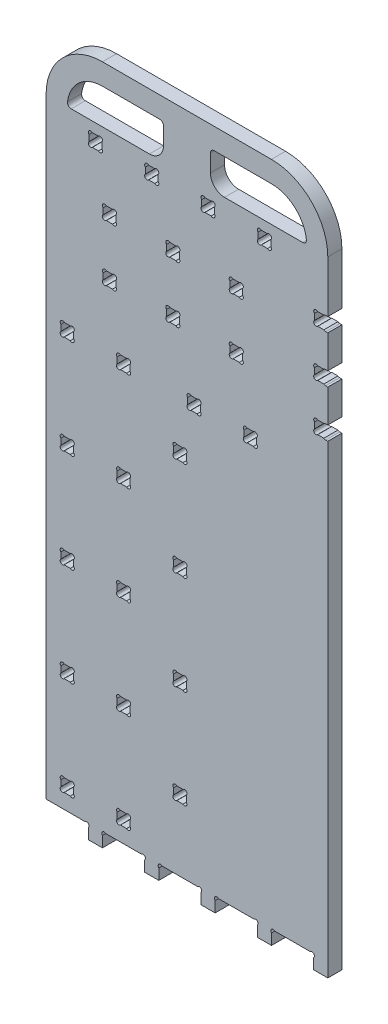
SolidWorks part; units mm, degrees
ref_plane "Front Plane" through (0, 0, 0) normal (0, 0, 1) x (1, 0, 0)
ref_plane "Top Plane" through (0, 0, 0) normal (0, 1, 0) x (1, 0, 0)
ref_plane "Right Plane" through (0, 0, 0) normal (1, 0, 0) x (0, 0, -1)
sketch "Sketch1" plane through (0, 0, 0) normal (0, 0, 1) x (1, 0, 0)
  line L0 (76.2, 869.95) -> (304.8, 869.95)
  line L1 (381, 793.75) -> (381, 723.9)
  line L11 (381, -50.8) -> (361.95, -50.8)
  line L12 (361.95, -50.8) -> (361.95, -36.2401)
  line L13 (309.2901, -31.75) -> (357.4599, -31.75)
  line L14 (304.8, -50.8) -> (304.8, -36.2401)
  line L15 (285.75, -50.8) -> (285.75, -36.2401)
  line L16 (233.0901, -31.75) -> (281.2599, -31.75)
  line L17 (228.6, -50.8) -> (228.6, -36.2401)
  line L18 (209.55, -50.8) -> (209.55, -36.2401)
  line L19 (156.8901, -31.75) -> (205.0599, -31.75)
  line L20 (152.4, -50.8) -> (152.4, -36.2401)
  line L21 (133.35, -50.8) -> (133.35, -36.2401)
  line L22 (80.6901, -31.75) -> (128.8599, -31.75)
  line L23 (76.2, -50.8) -> (76.2, -36.2401)
  line L24 (57.15, -50.8) -> (57.15, -36.2401)
  line L25 (381, -50.8) -> (381, 577.85)
  line L26 (52.6599, -31.75) -> (0, -31.75)
  line L27 (381, 704.85) -> (381, 660.4)
  line L28 (0, -31.75) -> (0, 793.75)
  line L29 (158.75, 812.8) -> (158.75, 836.295)
  line L30 (153.67, 841.375) -> (76.2, 841.375)
  line L31 (33.9594, 793.75) -> (139.7, 793.75)
  line L32 (227.33, 841.375) -> (304.8, 841.375)
  line L33 (347.0406, 793.75) -> (241.3, 793.75)
  line L34 (222.25, 812.8) -> (222.25, 836.295)
  line L35 (95.25, -12.7) -> (114.3, 6.35) construction
  line L36 (96.139, -11.811) -> (113.411, -11.811)
  line L37 (96.139, -11.811) -> (96.139, 5.461)
  line L38 (96.139, 5.461) -> (113.411, 5.461)
  line L39 (113.411, -11.811) -> (113.411, 5.461)
  line L40 (95.25, 6.35) -> (114.3, -12.7) construction
  line L41 (96.139, -7.3209) -> (100.6291, -11.811) construction
  line L42 (19.939, -11.811) -> (37.211, -11.811)
  line L43 (19.939, -11.811) -> (19.939, 5.461)
  line L44 (19.939, 5.461) -> (37.211, 5.461)
  line L45 (37.211, -11.811) -> (37.211, 5.461)
  line L46 (19.05, -12.7) -> (38.1, 6.35) construction
  line L47 (19.05, 6.35) -> (38.1, -12.7) construction
  line L48 (19.939, -7.3209) -> (24.4291, -11.811) construction
  line L49 (19.939, 121.539) -> (37.211, 121.539)
  line L50 (19.939, 121.539) -> (19.939, 138.811)
  line L51 (19.939, 138.811) -> (37.211, 138.811)
  line L52 (37.211, 121.539) -> (37.211, 138.811)
  line L53 (19.05, 120.65) -> (38.1, 139.7) construction
  line L54 (19.05, 139.7) -> (38.1, 120.65) construction
  line L55 (19.939, 126.0291) -> (24.4291, 121.539) construction
  line L56 (19.939, 254.889) -> (37.211, 254.889)
  line L57 (19.939, 254.889) -> (19.939, 272.161)
  line L58 (19.939, 272.161) -> (37.211, 272.161)
  line L59 (37.211, 254.889) -> (37.211, 272.161)
  line L60 (19.05, 254) -> (38.1, 273.05) construction
  line L61 (19.05, 273.05) -> (38.1, 254) construction
  line L62 (19.939, 259.3791) -> (24.4291, 254.889) construction
  line L63 (19.939, 388.239) -> (37.211, 388.239)
  line L64 (19.939, 388.239) -> (19.939, 405.511)
  line L65 (19.939, 405.511) -> (37.211, 405.511)
  line L66 (37.211, 388.239) -> (37.211, 405.511)
  line L67 (19.05, 387.35) -> (38.1, 406.4) construction
  line L68 (19.05, 406.4) -> (38.1, 387.35) construction
  line L69 (19.939, 392.7291) -> (24.4291, 388.239) construction
  line L70 (19.939, 521.589) -> (37.211, 521.589)
  line L71 (19.939, 521.589) -> (19.939, 538.861)
  line L72 (19.939, 538.861) -> (37.211, 538.861)
  line L73 (37.211, 521.589) -> (37.211, 538.861)
  line L74 (19.05, 520.7) -> (38.1, 539.75) construction
  line L94 (191.389, 521.589) -> (208.661, 521.589)
  line L95 (191.389, 521.589) -> (191.389, 538.861)
  line L96 (191.389, 538.861) -> (208.661, 538.861)
  line L97 (208.661, 521.589) -> (208.661, 538.861)
  line L98 (267.589, 521.589) -> (284.861, 521.589)
  line L99 (267.589, 521.589) -> (267.589, 538.861)
  line L100 (267.589, 538.861) -> (284.861, 538.861)
  line L101 (284.861, 521.589) -> (284.861, 538.861)
  line L147 (285.75, -50.8) -> (304.8, -50.8)
  line L148 (209.55, -50.8) -> (228.6, -50.8)
  line L149 (133.35, -50.8) -> (152.4, -50.8)
  line L150 (57.15, -50.8) -> (76.2, -50.8)
  line L152 (381, 641.35) -> (381, 596.9)
  line L153 (172.339, 188.214) -> (189.611, 188.214)
  line L154 (0, -50.8) -> (0, -36.2401) [skipped]
  line L155 (4.4901, -31.75) -> (52.6599, -31.75) [skipped]
  line L156 (172.339, 188.214) -> (172.339, 205.486)
  line L157 (172.339, 205.486) -> (189.611, 205.486)
  line L158 (189.611, 188.214) -> (189.611, 205.486)
  line L163 (173.6951, 189.5701) -> (188.2549, 189.5701) construction
  line L164 (173.6951, 189.5701) -> (173.6951, 204.1299) construction
  line L165 (173.6951, 204.1299) -> (188.2549, 204.1299) construction
  line L166 (188.2549, 189.5701) -> (188.2549, 204.1299) construction
  line L171 (173.6951, 56.2201) -> (188.2549, 56.2201) construction
  line L172 (173.6951, 56.2201) -> (173.6951, 70.7799) construction
  line L173 (173.6951, 70.7799) -> (188.2549, 70.7799) construction
  line L174 (188.2549, 56.2201) -> (188.2549, 70.7799) construction
  line L175 (190.5, 520.7) -> (209.55, 539.75) construction
  line L176 (190.5, 539.75) -> (209.55, 520.7) construction
  line L177 (191.389, 526.0791) -> (195.8791, 521.589) construction
  line L178 (266.7, 520.7) -> (285.75, 539.75) construction
  line L179 (266.7, 539.75) -> (285.75, 520.7) construction
  line L180 (267.589, 526.0791) -> (272.0791, 521.589) construction
  line L181 (171.45, 53.975) -> (190.5, 73.025) construction
  line L182 (172.339, 54.864) -> (189.611, 54.864)
  line L183 (172.339, 54.864) -> (172.339, 72.136)
  line L184 (172.339, 72.136) -> (189.611, 72.136)
  line L185 (189.611, 54.864) -> (189.611, 72.136)
  line L186 (171.45, 73.025) -> (190.5, 53.975) construction
  line L187 (172.339, 59.3541) -> (176.8291, 54.864) construction
  line L188 (171.45, 187.325) -> (190.5, 206.375) construction
  line L189 (171.45, 206.375) -> (190.5, 187.325) construction
  line L190 (172.339, 192.7041) -> (176.8291, 188.214) construction
  line L191 (172.339, 321.564) -> (189.611, 321.564)
  line L192 (172.339, 321.564) -> (172.339, 338.836)
  line L193 (172.339, 338.836) -> (189.611, 338.836)
  line L194 (189.611, 321.564) -> (189.611, 338.836)
  line L195 (173.6951, 322.9201) -> (188.2549, 322.9201) construction
  line L196 (173.6951, 322.9201) -> (173.6951, 337.4799) construction
  line L197 (173.6951, 337.4799) -> (188.2549, 337.4799) construction
  line L198 (188.2549, 322.9201) -> (188.2549, 337.4799) construction
  line L199 (19.05, 539.75) -> (38.1, 520.7) construction
  line L200 (19.939, 526.0791) -> (24.4291, 521.589) construction
  line L201 (96.139, 121.539) -> (113.411, 121.539)
  line L202 (96.139, 121.539) -> (96.139, 138.811)
  line L203 (96.139, 138.811) -> (113.411, 138.811)
  line L204 (113.411, 121.539) -> (113.411, 138.811)
  line L205 (95.25, 120.65) -> (114.3, 139.7) construction
  line L206 (95.25, 139.7) -> (114.3, 120.65) construction
  line L207 (96.139, 126.0291) -> (100.6291, 121.539) construction
  line L208 (96.139, 254.889) -> (113.411, 254.889)
  line L209 (96.139, 254.889) -> (96.139, 272.161)
  line L210 (96.139, 272.161) -> (113.411, 272.161)
  line L211 (113.411, 254.889) -> (113.411, 272.161)
  line L212 (95.25, 254) -> (114.3, 273.05) construction
  line L213 (95.25, 273.05) -> (114.3, 254) construction
  line L214 (96.139, 259.3791) -> (100.6291, 254.889) construction
  line L215 (96.139, 388.239) -> (113.411, 388.239)
  line L216 (96.139, 388.239) -> (96.139, 405.511)
  line L217 (96.139, 405.511) -> (113.411, 405.511)
  line L218 (113.411, 388.239) -> (113.411, 405.511)
  line L219 (95.25, 387.35) -> (114.3, 406.4) construction
  line L220 (95.25, 406.4) -> (114.3, 387.35) construction
  line L221 (96.139, 392.7291) -> (100.6291, 388.239) construction
  line L222 (96.139, 521.589) -> (113.411, 521.589)
  line L223 (96.139, 521.589) -> (96.139, 538.861)
  line L224 (96.139, 538.861) -> (113.411, 538.861)
  line L225 (113.411, 521.589) -> (113.411, 538.861)
  line L226 (95.25, 520.7) -> (114.3, 539.75) construction
  line L227 (95.25, 539.75) -> (114.3, 520.7) construction
  line L228 (96.139, 526.0791) -> (100.6291, 521.589) construction
  line L229 (285.75, 762) -> (304.8, 781.05) construction
  line L230 (286.639, 762.889) -> (303.911, 762.889)
  line L231 (286.639, 762.889) -> (286.639, 780.161)
  line L232 (286.639, 780.161) -> (303.911, 780.161)
  line L233 (303.911, 762.889) -> (303.911, 780.161)
  line L234 (285.75, 781.05) -> (304.8, 762) construction
  line L235 (286.639, 767.3791) -> (291.1291, 762.889) construction
  line L236 (210.439, 762.889) -> (227.711, 762.889)
  line L237 (210.439, 762.889) -> (210.439, 780.161)
  line L238 (210.439, 780.161) -> (227.711, 780.161)
  line L239 (227.711, 762.889) -> (227.711, 780.161)
  line L240 (209.55, 762) -> (228.6, 781.05) construction
  line L241 (209.55, 781.05) -> (228.6, 762) construction
  line L242 (171.45, 320.675) -> (190.5, 339.725) construction
  line L243 (171.45, 339.725) -> (190.5, 320.675) construction
  line L244 (172.339, 326.0541) -> (176.8291, 321.564) construction
  line L245 (172.339, 454.914) -> (189.611, 454.914)
  line L246 (172.339, 454.914) -> (172.339, 472.186)
  line L247 (172.339, 472.186) -> (189.611, 472.186)
  line L248 (189.611, 454.914) -> (189.611, 472.186)
  line L249 (173.6951, 456.2701) -> (188.2549, 456.2701) construction
  line L250 (173.6951, 456.2701) -> (173.6951, 470.8299) construction
  line L251 (173.6951, 470.8299) -> (188.2549, 470.8299) construction
  line L252 (188.2549, 456.2701) -> (188.2549, 470.8299) construction
  line L253 (171.45, 454.025) -> (190.5, 473.075) construction
  line L254 (171.45, 473.075) -> (190.5, 454.025) construction
  line L255 (172.339, 459.4041) -> (176.8291, 454.914) construction
  line L256 (247.65, 685.8) -> (266.7, 704.85) construction
  line L257 (248.539, 686.689) -> (265.811, 686.689)
  line L258 (248.539, 686.689) -> (248.539, 703.961)
  line L259 (248.539, 703.961) -> (265.811, 703.961)
  line L260 (265.811, 686.689) -> (265.811, 703.961)
  line L261 (247.65, 704.85) -> (266.7, 685.8) construction
  line L262 (248.539, 691.1791) -> (253.0291, 686.689) construction
  line L263 (162.814, 686.689) -> (180.086, 686.689)
  line L264 (162.814, 686.689) -> (162.814, 703.961)
  line L265 (162.814, 703.961) -> (180.086, 703.961)
  line L266 (180.086, 686.689) -> (180.086, 703.961)
  line L267 (161.925, 685.8) -> (180.975, 704.85) construction
  line L268 (161.925, 704.85) -> (180.975, 685.8) construction
  line L269 (162.814, 691.1791) -> (167.3041, 686.689) construction
  line L270 (77.089, 686.689) -> (94.361, 686.689)
  line L271 (77.089, 686.689) -> (77.089, 703.961)
  line L272 (77.089, 703.961) -> (94.361, 703.961)
  line L273 (94.361, 686.689) -> (94.361, 703.961)
  line L274 (76.2, 685.8) -> (95.25, 704.85) construction
  line L275 (76.2, 704.85) -> (95.25, 685.8) construction
  line L276 (77.089, 691.1791) -> (81.5791, 686.689) construction
  line L277 (162.814, 610.489) -> (180.086, 610.489)
  line L278 (162.814, 610.489) -> (162.814, 627.761)
  line L279 (162.814, 627.761) -> (180.086, 627.761)
  line L280 (180.086, 610.489) -> (180.086, 627.761)
  line L281 (161.925, 609.6) -> (180.975, 628.65) construction
  line L282 (161.925, 628.65) -> (180.975, 609.6) construction
  line L283 (162.814, 614.9791) -> (167.3041, 610.489) construction
  line L284 (77.089, 610.489) -> (94.361, 610.489)
  line L285 (77.089, 610.489) -> (77.089, 627.761)
  line L286 (77.089, 627.761) -> (94.361, 627.761)
  line L287 (94.361, 610.489) -> (94.361, 627.761)
  line L288 (76.2, 609.6) -> (95.25, 628.65) construction
  line L289 (76.2, 628.65) -> (95.25, 609.6) construction
  line L290 (77.089, 614.9791) -> (81.5791, 610.489) construction
  line L291 (248.539, 610.489) -> (265.811, 610.489)
  line L292 (248.539, 610.489) -> (248.539, 627.761)
  line L293 (248.539, 627.761) -> (265.811, 627.761)
  line L294 (265.811, 610.489) -> (265.811, 627.761)
  line L295 (247.65, 609.6) -> (266.7, 628.65) construction
  line L296 (247.65, 628.65) -> (266.7, 609.6) construction
  line L297 (248.539, 614.9791) -> (253.0291, 610.489) construction
  line L298 (210.439, 767.3791) -> (214.9291, 762.889) construction
  line L299 (134.239, 762.889) -> (151.511, 762.889)
  line L300 (134.239, 762.889) -> (134.239, 780.161)
  line L301 (134.239, 780.161) -> (151.511, 780.161)
  line L302 (151.511, 762.889) -> (151.511, 780.161)
  line L303 (133.35, 762) -> (152.4, 781.05) construction
  line L304 (133.35, 781.05) -> (152.4, 762) construction
  line L305 (134.239, 767.3791) -> (138.7291, 762.889) construction
  line L306 (58.039, 762.889) -> (75.311, 762.889)
  line L307 (58.039, 762.889) -> (58.039, 780.161)
  line L308 (58.039, 780.161) -> (75.311, 780.161)
  line L309 (75.311, 762.889) -> (75.311, 780.161)
  line L310 (57.15, 762) -> (76.2, 781.05) construction
  line L311 (57.15, 781.05) -> (76.2, 762) construction
  line L312 (58.039, 767.3791) -> (62.5291, 762.889) construction
  line L313 (366.4401, 577.85) -> (376.5099, 596.9) construction
  line L314 (362.839, 578.739) -> (380.111, 578.739)
  line L315 (362.839, 578.739) -> (362.839, 596.011)
  line L316 (362.839, 596.011) -> (380.111, 596.011)
  line L317 (380.111, 578.739) -> (380.111, 596.011)
  line L318 (361.95, 577.85) -> (381, 596.9) construction
  line L319 (361.95, 596.9) -> (381, 577.85) construction
  line L320 (362.839, 583.2291) -> (367.3291, 578.739) construction
  line L321 (381, 660.4) -> (377.8659, 660.4409)
  line L322 (377.8659, 641.3091) -> (381, 641.35)
  line L323 (381, 577.85) -> (381, 596.9)
  line L324 (366.4401, 641.35) -> (376.5099, 660.4) construction
  line L325 (362.839, 642.239) -> (380.111, 642.239)
  line L326 (362.839, 642.239) -> (362.839, 659.511)
  line L327 (362.839, 659.511) -> (380.111, 659.511)
  line L328 (380.111, 642.239) -> (380.111, 659.511)
  line L329 (361.95, 641.35) -> (381, 660.4) construction
  line L330 (361.95, 660.4) -> (381, 641.35) construction
  line L331 (362.839, 646.7291) -> (367.3291, 642.239) construction
  line L332 (377.8659, 596.9409) -> (381, 596.9)
  line L333 (377.8659, 577.8091) -> (381, 577.85)
  line L334 (377.8659, 723.9409) -> (381, 723.9)
  line L335 (381, 704.85) -> (377.3577, 704.85)
  line L336 (366.4401, 704.85) -> (376.5099, 723.9) construction
  line L337 (362.839, 705.739) -> (380.111, 705.739)
  line L338 (362.839, 705.739) -> (362.839, 723.011)
  line L339 (362.839, 723.011) -> (380.111, 723.011)
  line L340 (380.111, 705.739) -> (380.111, 723.011)
  line L341 (362.839, 710.2291) -> (367.3291, 705.739) construction
  arc A0 (0, 793.75) -> (76.2, 869.95) centre (76.2, 793.75) cw
  arc A1 (304.8, 869.95) -> (381, 793.75) centre (304.8, 793.75) cw
  arc A14 (361.95, -36.2401) -> (357.4599, -31.75) centre (359.7049, -33.9951) ccw
  arc A15 (309.2901, -31.75) -> (304.8, -36.2401) centre (307.0451, -33.9951) ccw
  arc A16 (285.75, -36.2401) -> (281.2599, -31.75) centre (283.5049, -33.9951) ccw
  arc A17 (233.0901, -31.75) -> (228.6, -36.2401) centre (230.8451, -33.9951) ccw
  arc A18 (209.55, -36.2401) -> (205.0599, -31.75) centre (207.3049, -33.9951) ccw
  arc A19 (156.8901, -31.75) -> (152.4, -36.2401) centre (154.6451, -33.9951) ccw
  arc A20 (133.35, -36.2401) -> (128.8599, -31.75) centre (131.1049, -33.9951) ccw
  arc A21 (80.6901, -31.75) -> (76.2, -36.2401) centre (78.4451, -33.9951) ccw
  arc A22 (57.15, -36.2401) -> (52.6599, -31.75) centre (54.9049, -33.9951) ccw
  arc A23 (158.75, 836.295) -> (153.67, 841.375) centre (153.67, 836.295) ccw
  arc A25 (76.2, 841.375) -> (28.9157, 799.4366) centre (76.2, 793.75) ccw
  arc A27 (139.7, 793.75) -> (158.75, 812.8) centre (139.7, 812.8) ccw
  arc A28 (304.8, 841.375) -> (352.0843, 799.4366) centre (304.8, 793.75) cw
  arc A29 (241.3, 793.75) -> (222.25, 812.8) centre (241.3, 812.8) cw
  arc A30 (352.0843, 799.4366) -> (347.0406, 793.75) centre (347.0406, 798.83) cw
  arc A31 (222.25, 836.295) -> (227.33, 841.375) centre (227.33, 836.295) cw
  arc A32 (33.9594, 793.75) -> (28.9157, 799.4366) centre (33.9594, 798.83) cw
  arc A154 (4.4901, -31.75) -> (0, -36.2401) centre (2.2451, -33.9951) ccw [skipped]
  arc A155 (96.139, 0.9709) -> (100.6291, 5.461) centre (98.3841, 3.2159) cw
  arc A156 (108.9209, 5.461) -> (113.411, 0.9709) centre (111.1659, 3.2159) cw
  arc A157 (96.139, -7.3209) -> (100.6291, -11.811) centre (98.3841, -9.5659) ccw
  arc A158 (113.411, -7.3209) -> (108.9209, -11.811) centre (111.1659, -9.5659) cw
  arc A159 (19.939, 0.9709) -> (24.4291, 5.461) centre (22.1841, 3.2159) cw
  arc A160 (32.7209, 5.461) -> (37.211, 0.9709) centre (34.9659, 3.2159) cw
  arc A161 (19.939, -7.3209) -> (24.4291, -11.811) centre (22.1841, -9.5659) ccw
  arc A188 (191.389, 534.3709) -> (195.8791, 538.861) centre (193.6341, 536.6159) cw
  arc A189 (204.1709, 538.861) -> (208.661, 534.3709) centre (206.4159, 536.6159) cw
  arc A190 (37.211, -7.3209) -> (32.7209, -11.811) centre (34.9659, -9.5659) cw
  arc A192 (19.939, 134.3209) -> (24.4291, 138.811) centre (22.1841, 136.5659) cw
  arc A193 (32.7209, 138.811) -> (37.211, 134.3209) centre (34.9659, 136.5659) cw
  arc A194 (19.939, 126.0291) -> (24.4291, 121.539) centre (22.1841, 123.7841) ccw
  arc A195 (37.211, 126.0291) -> (32.7209, 121.539) centre (34.9659, 123.7841) cw
  arc A197 (19.939, 267.6709) -> (24.4291, 272.161) centre (22.1841, 269.9159) cw
  arc A198 (32.7209, 272.161) -> (37.211, 267.6709) centre (34.9659, 269.9159) cw
  arc A199 (19.939, 259.3791) -> (24.4291, 254.889) centre (22.1841, 257.1341) ccw
  arc A200 (37.211, 259.3791) -> (32.7209, 254.889) centre (34.9659, 257.1341) cw
  arc A202 (19.939, 401.0209) -> (24.4291, 405.511) centre (22.1841, 403.2659) cw
  arc A203 (32.7209, 405.511) -> (37.211, 401.0209) centre (34.9659, 403.2659) cw
  arc A204 (19.939, 392.7291) -> (24.4291, 388.239) centre (22.1841, 390.4841) ccw
  arc A205 (37.211, 392.7291) -> (32.7209, 388.239) centre (34.9659, 390.4841) cw
  arc A207 (19.939, 534.3709) -> (24.4291, 538.861) centre (22.1841, 536.6159) cw
  arc A208 (32.7209, 538.861) -> (37.211, 534.3709) centre (34.9659, 536.6159) cw
  arc A209 (19.939, 526.0791) -> (24.4291, 521.589) centre (22.1841, 523.8341) ccw
  arc A210 (37.211, 526.0791) -> (32.7209, 521.589) centre (34.9659, 523.8341) cw
  arc A212 (96.139, 134.3209) -> (100.6291, 138.811) centre (98.3841, 136.5659) cw
  arc A213 (108.9209, 138.811) -> (113.411, 134.3209) centre (111.1659, 136.5659) cw
  arc A214 (96.139, 126.0291) -> (100.6291, 121.539) centre (98.3841, 123.7841) ccw
  arc A215 (113.411, 126.0291) -> (108.9209, 121.539) centre (111.1659, 123.7841) cw
  arc A217 (96.139, 267.6709) -> (100.6291, 272.161) centre (98.3841, 269.9159) cw
  arc A218 (108.9209, 272.161) -> (113.411, 267.6709) centre (111.1659, 269.9159) cw
  arc A219 (96.139, 259.3791) -> (100.6291, 254.889) centre (98.3841, 257.1341) ccw
  arc A220 (113.411, 259.3791) -> (108.9209, 254.889) centre (111.1659, 257.1341) cw
  arc A222 (96.139, 401.0209) -> (100.6291, 405.511) centre (98.3841, 403.2659) cw
  arc A223 (108.9209, 405.511) -> (113.411, 401.0209) centre (111.1659, 403.2659) cw
  arc A224 (96.139, 392.7291) -> (100.6291, 388.239) centre (98.3841, 390.4841) ccw
  arc A225 (113.411, 392.7291) -> (108.9209, 388.239) centre (111.1659, 390.4841) cw
  arc A227 (96.139, 534.3709) -> (100.6291, 538.861) centre (98.3841, 536.6159) cw
  arc A228 (108.9209, 538.861) -> (113.411, 534.3709) centre (111.1659, 536.6159) cw
  arc A229 (96.139, 526.0791) -> (100.6291, 521.589) centre (98.3841, 523.8341) ccw
  arc A230 (113.411, 526.0791) -> (108.9209, 521.589) centre (111.1659, 523.8341) cw
  arc A232 (172.339, 67.6459) -> (176.8291, 72.136) centre (174.5841, 69.8909) cw
  arc A233 (191.389, 526.0791) -> (195.8791, 521.589) centre (193.6341, 523.8341) ccw
  arc A234 (208.661, 526.0791) -> (204.1709, 521.589) centre (206.4159, 523.8341) cw
  arc A235 (267.589, 534.3709) -> (272.0791, 538.861) centre (269.8341, 536.6159) cw
  arc A236 (280.3709, 538.861) -> (284.861, 534.3709) centre (282.6159, 536.6159) cw
  arc A237 (267.589, 526.0791) -> (272.0791, 521.589) centre (269.8341, 523.8341) ccw
  arc A238 (284.861, 526.0791) -> (280.3709, 521.589) centre (282.6159, 523.8341) cw
  arc A239 (185.1209, 72.136) -> (189.611, 67.6459) centre (187.3659, 69.8909) cw
  arc A240 (172.339, 59.3541) -> (176.8291, 54.864) centre (174.5841, 57.1091) ccw
  arc A241 (189.611, 59.3541) -> (185.1209, 54.864) centre (187.3659, 57.1091) cw
  arc A242 (286.639, 775.6709) -> (291.1291, 780.161) centre (288.8841, 777.9159) cw
  arc A243 (299.4209, 780.161) -> (303.911, 775.6709) centre (301.6659, 777.9159) cw
  arc A244 (286.639, 767.3791) -> (291.1291, 762.889) centre (288.8841, 765.1341) ccw
  arc A245 (303.911, 767.3791) -> (299.4209, 762.889) centre (301.6659, 765.1341) cw
  arc A246 (210.439, 775.6709) -> (214.9291, 780.161) centre (212.6841, 777.9159) cw
  arc A247 (223.2209, 780.161) -> (227.711, 775.6709) centre (225.4659, 777.9159) cw
  arc A248 (172.339, 200.9959) -> (176.8291, 205.486) centre (174.5841, 203.2409) cw
  arc A249 (185.1209, 205.486) -> (189.611, 200.9959) centre (187.3659, 203.2409) cw
  arc A250 (172.339, 192.7041) -> (176.8291, 188.214) centre (174.5841, 190.4591) ccw
  arc A251 (189.611, 192.7041) -> (185.1209, 188.214) centre (187.3659, 190.4591) cw
  arc A252 (172.339, 334.3459) -> (176.8291, 338.836) centre (174.5841, 336.5909) cw
  arc A253 (185.1209, 338.836) -> (189.611, 334.3459) centre (187.3659, 336.5909) cw
  arc A254 (172.339, 326.0541) -> (176.8291, 321.564) centre (174.5841, 323.8091) ccw
  arc A255 (189.611, 326.0541) -> (185.1209, 321.564) centre (187.3659, 323.8091) cw
  arc A256 (172.339, 467.6959) -> (176.8291, 472.186) centre (174.5841, 469.9409) cw
  arc A257 (185.1209, 472.186) -> (189.611, 467.6959) centre (187.3659, 469.9409) cw
  arc A258 (172.339, 459.4041) -> (176.8291, 454.914) centre (174.5841, 457.1591) ccw
  arc A259 (189.611, 459.4041) -> (185.1209, 454.914) centre (187.3659, 457.1591) cw
  arc A260 (248.539, 699.4709) -> (253.0291, 703.961) centre (250.7841, 701.7159) cw
  arc A261 (261.3209, 703.961) -> (265.811, 699.4709) centre (263.5659, 701.7159) cw
  arc A262 (248.539, 691.1791) -> (253.0291, 686.689) centre (250.7841, 688.9341) ccw
  arc A263 (265.811, 691.1791) -> (261.3209, 686.689) centre (263.5659, 688.9341) cw
  arc A264 (162.814, 699.4709) -> (167.3041, 703.961) centre (165.0591, 701.7159) cw
  arc A265 (175.5959, 703.961) -> (180.086, 699.4709) centre (177.8409, 701.7159) cw
  arc A266 (162.814, 691.1791) -> (167.3041, 686.689) centre (165.0591, 688.9341) ccw
  arc A267 (180.086, 691.1791) -> (175.5959, 686.689) centre (177.8409, 688.9341) cw
  arc A268 (77.089, 699.4709) -> (81.5791, 703.961) centre (79.3341, 701.7159) cw
  arc A269 (89.8709, 703.961) -> (94.361, 699.4709) centre (92.1159, 701.7159) cw
  arc A270 (77.089, 691.1791) -> (81.5791, 686.689) centre (79.3341, 688.9341) ccw
  arc A271 (94.361, 691.1791) -> (89.8709, 686.689) centre (92.1159, 688.9341) cw
  arc A272 (162.814, 623.2709) -> (167.3041, 627.761) centre (165.0591, 625.5159) cw
  arc A273 (175.5959, 627.761) -> (180.086, 623.2709) centre (177.8409, 625.5159) cw
  arc A274 (162.814, 614.9791) -> (167.3041, 610.489) centre (165.0591, 612.7341) ccw
  arc A275 (180.086, 614.9791) -> (175.5959, 610.489) centre (177.8409, 612.7341) cw
  arc A276 (77.089, 623.2709) -> (81.5791, 627.761) centre (79.3341, 625.5159) cw
  arc A277 (89.8709, 627.761) -> (94.361, 623.2709) centre (92.1159, 625.5159) cw
  arc A278 (77.089, 614.9791) -> (81.5791, 610.489) centre (79.3341, 612.7341) ccw
  arc A279 (94.361, 614.9791) -> (89.8709, 610.489) centre (92.1159, 612.7341) cw
  arc A280 (248.539, 623.2709) -> (253.0291, 627.761) centre (250.7841, 625.5159) cw
  arc A281 (261.3209, 627.761) -> (265.811, 623.2709) centre (263.5659, 625.5159) cw
  arc A282 (248.539, 614.9791) -> (253.0291, 610.489) centre (250.7841, 612.7341) ccw
  arc A283 (265.811, 614.9791) -> (261.3209, 610.489) centre (263.5659, 612.7341) cw
  arc A284 (210.439, 767.3791) -> (214.9291, 762.889) centre (212.6841, 765.1341) ccw
  arc A285 (227.711, 767.3791) -> (223.2209, 762.889) centre (225.4659, 765.1341) cw
  arc A286 (134.239, 775.6709) -> (138.7291, 780.161) centre (136.4841, 777.9159) cw
  arc A287 (147.0209, 780.161) -> (151.511, 775.6709) centre (149.2659, 777.9159) cw
  arc A288 (134.239, 767.3791) -> (138.7291, 762.889) centre (136.4841, 765.1341) ccw
  arc A289 (151.511, 767.3791) -> (147.0209, 762.889) centre (149.2659, 765.1341) cw
  arc A290 (58.039, 775.6709) -> (62.5291, 780.161) centre (60.2841, 777.9159) cw
  arc A291 (70.8209, 780.161) -> (75.311, 775.6709) centre (73.0659, 777.9159) cw
  arc A292 (58.039, 767.3791) -> (62.5291, 762.889) centre (60.2841, 765.1341) ccw
  arc A293 (75.311, 767.3791) -> (70.8209, 762.889) centre (73.0659, 765.1341) cw
  arc A294 (362.839, 591.5209) -> (367.3291, 596.011) centre (365.0841, 593.7659) cw
  arc A295 (375.6209, 596.011) -> (380.111, 591.5209) centre (377.8659, 593.7659) cw
  arc A296 (362.839, 583.2291) -> (367.3291, 578.739) centre (365.0841, 580.9841) ccw
  arc A297 (380.111, 583.2291) -> (375.6209, 578.739) centre (377.8659, 580.9841) cw
  arc A298 (362.839, 718.5209) -> (367.3291, 723.011) centre (365.0841, 720.7659) cw
  arc A299 (375.6209, 723.011) -> (380.111, 718.5209) centre (377.8659, 720.7659) cw
  arc A300 (362.839, 710.2291) -> (367.3291, 705.739) centre (365.0841, 707.9841) ccw
  arc A301 (380.111, 710.2291) -> (375.6209, 705.739) centre (377.8659, 707.9841) cw
  arc A302 (362.839, 655.0209) -> (367.3291, 659.511) centre (365.0841, 657.2659) cw
  arc A303 (375.6209, 659.511) -> (380.111, 655.0209) centre (377.8659, 657.2659) cw
  arc A304 (362.839, 646.7291) -> (367.3291, 642.239) centre (365.0841, 644.4841) ccw
  arc A305 (380.111, 646.7291) -> (375.6209, 642.239) centre (377.8659, 644.4841) cw
  point P12 (104.775, -3.175)
  point P47 (371.475, 650.875)
  point P109 (28.575, -3.175)
  point P146 (200.025, 530.225)
  point P150 (28.575, 130.175)
  point P176 (28.575, 263.525)
  point P203 (28.575, 396.875)
  point P216 (180.975, 196.85)
  point P258 (28.575, 530.225)
  point P281 (104.775, 130.175)
  point P305 (104.775, 263.525)
  point P328 (104.775, 396.875)
  point P334 (180.975, 330.2)
  point P361 (276.225, 530.225)
  point P383 (295.275, 771.525)
  point P396 (180.975, 63.5)
  point P400 (104.775, 530.225)
  point P421 (219.075, 771.525)
  point P443 (142.875, 771.525)
  point P448 (257.175, 695.325)
  point P483 (171.45, 695.325)
  point P506 (85.725, 695.325)
  point P527 (171.45, 619.125)
  point P565 (66.675, 771.525)
  point P584 (371.475, 714.375)
  point P586 (371.475, 587.375)
  point P604 (180.975, 463.55)
  point P635 (85.725, 619.125)
  point P656 (257.175, 619.125)
  point P722 (380.111, 714.375)
  point P723 (371.475, 723.011)
  dimension "D3" = 5
  dimension "D6" = 2
  dimension "D9" = 6.35
  dimension "D18" = 3.175
  dimension "D8" = 3.175
  dimension "D7" = 17.272
  dimension "D10" = 6.35
  dimension "D16" = 825.5
  dimension "D17" = 14.5599
  dimension "D4" = 4
  dimension "D5" = 2
  dimension "D11" = 6.35
  dimension "D12" = 6.35
  dimension "D13" = 45
  dimension "D2" = 5
extrude "Boss-Extrude1" add sketch "Sketch1" along normal blind 19.05
